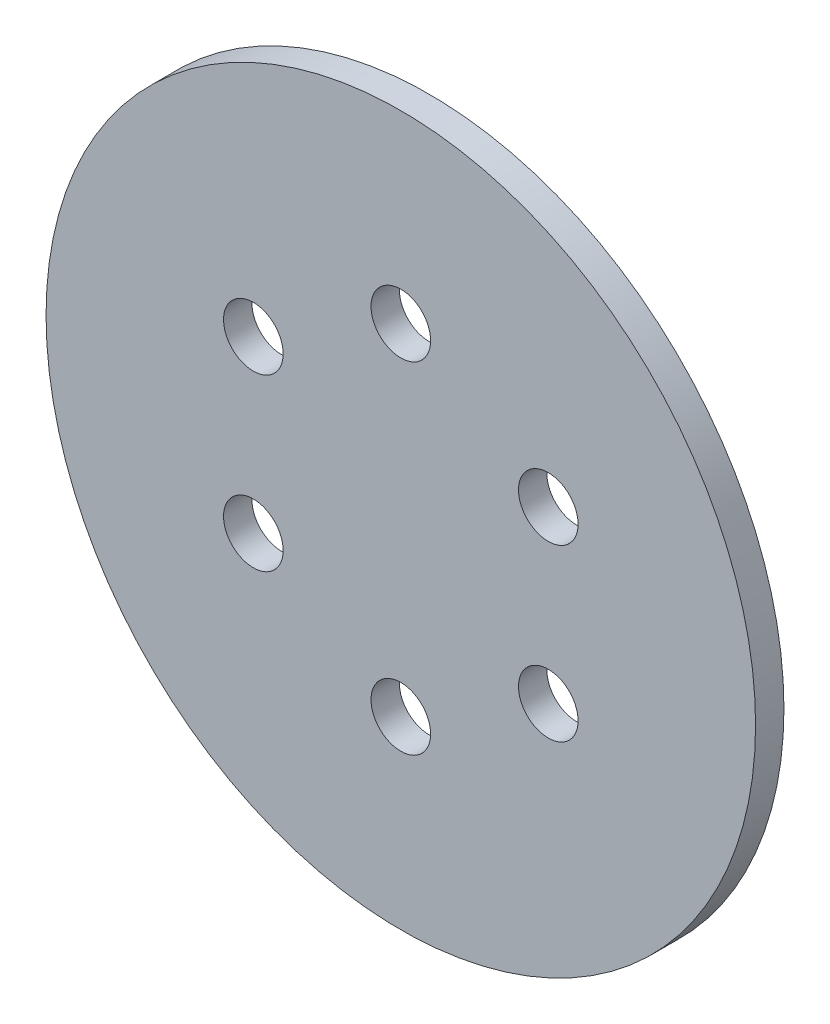
SolidWorks part; units mm, degrees
material "6061 合金"
ref_plane "前视基准面" through (0, 0, 0) normal (0, 0, 1) x (1, 0, 0)
ref_plane "上视基准面" through (0, 0, 0) normal (0, 1, 0) x (1, 0, 0)
ref_plane "右视基准面" through (0, 0, 0) normal (1, 0, 0) x (0, 0, -1)
other "Configuration Table"
sketch "草图1" plane through (0, 0, 0) normal (0, 0, 1) x (1, 0, 0)
  circle A0 centre (0, 0) radius 12 construction
  circle A1 centre (0, 12) radius 2.1
  circle A2 centre (10.3923, 6) radius 2.1
  circle A3 centre (10.3923, -6) radius 2.1
  circle A4 centre (0, -12) radius 2.1
  circle A5 centre (-10.3923, -6) radius 2.1
  circle A6 centre (-10.3923, 6) radius 2.1
  circle A7 centre (0, 0) radius 25
  point P17 (0, 0)
  dimension "D2" = 4.2
  dimension "D4" = 50
  dimension "D3" = 6
extrude "凸台-拉伸1" add sketch "草图1" along normal blind 2
sketch3d "3D草图1"
  point P0 (-6.6814, 17.1609, 2)
sketch3d "3D草图2"
  point P0 (-15.2718, 13.0248, 2)
ref_plane "基准面2" through (0, 0, 2) normal (0, 0, 1) x (1, 0, 0)
sketch "草图3" plane through (0, 0, 2) normal (0, 0, 1) x (1, 0, 0)
  circle A0 centre (0, 12) radius 3
  circle A1 centre (10.3923, 6) radius 3
  circle A2 centre (10.3923, -6) radius 3
  circle A3 centre (0, -12) radius 3
  circle A4 centre (-10.3923, -6) radius 3
  circle A5 centre (-10.3923, 6) radius 3
  circle A6 centre (-10.3923, 6) radius 2.1 construction
  point P15 (0, 0)
  dimension "D1" = 6
